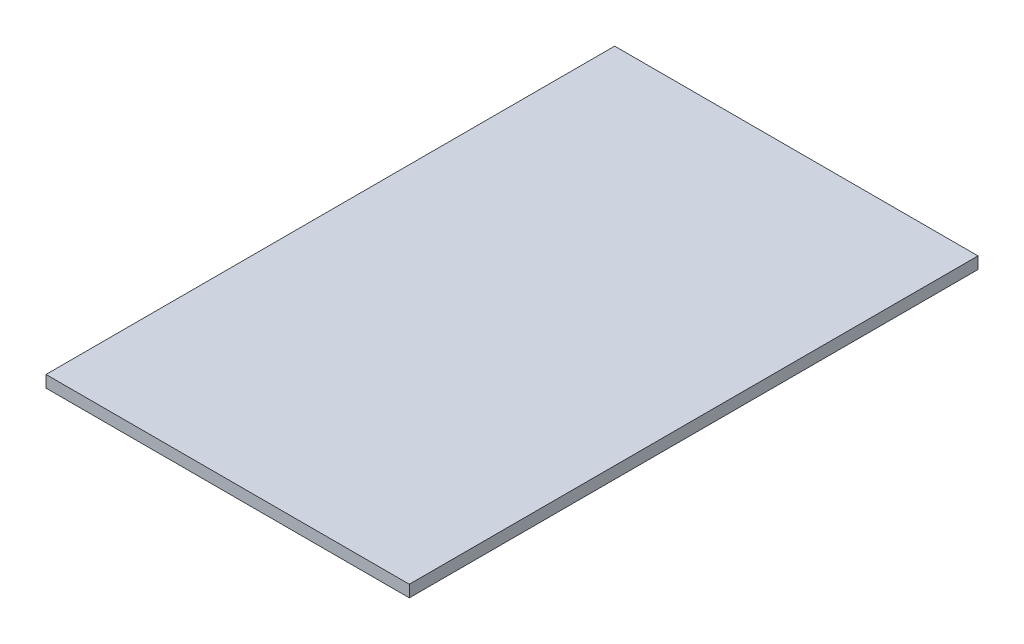
SolidWorks part; units mm, degrees
material "PVC Rigid"
ref_plane "Front Plane" through (0, 0, 0) normal (0, 0, 1) x (1, 0, 0)
ref_plane "Top Plane" through (0, 0, 0) normal (0, 1, 0) x (1, 0, 0)
ref_plane "Right Plane" through (0, 0, 0) normal (1, 0, 0) x (0, 0, -1)
sketch "Sketch1" plane through (0, 0, 0) normal (0, 1, 0) x (1, 0, 0)
  line L1 (-146.05, -228.6) -> (146.05, -228.6)
  line L2 (-146.05, -228.6) -> (-146.05, 228.6)
  line L3 (-146.05, 228.6) -> (146.05, 228.6)
  line L4 (146.05, -228.6) -> (146.05, 228.6)
  line L5 (-146.05, -228.6) -> (146.05, 228.6) construction
  line L6 (-146.05, 228.6) -> (146.05, -228.6) construction
  point P0 (0, 0)
  dimension "D1" = 457.2
  dimension "D2" = 292.1
extrude "Boss-Extrude1" add sketch "Sketch1" along normal mid plane 9.525
